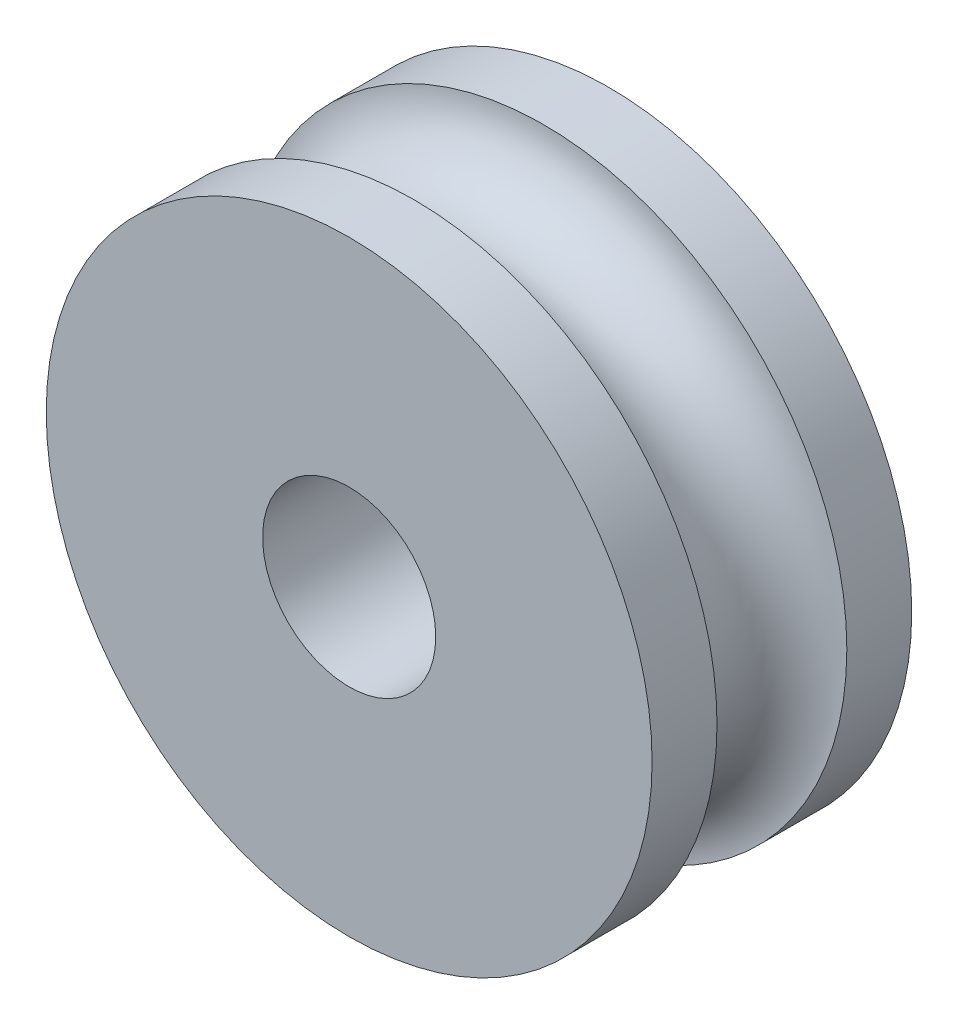
SolidWorks part; units mm, degrees
ref_plane "Alzado" through (0, 0, 0) normal (0, 0, 1) x (1, 0, 0)
ref_plane "Planta" through (0, 0, 0) normal (0, 1, 0) x (1, 0, 0)
ref_plane "Vista lateral" through (0, 0, 0) normal (1, 0, 0) x (0, 0, -1)
sketch "Croquis1" plane through (0, 0, 0) normal (0, 0, 1) x (1, 0, 0)
  circle A0 centre (0, 0) radius 3.5
  dimension "D1" = 7
extrude "Saliente-Extruir1" add sketch "Croquis1" along normal blind 3
ref_axis "Eje1" through (0, 0, 3) along (0, 0, -1)
sketch "Croquis2" plane through (0, 0, 0) normal (1, 0, 0) x (0, 0, -1)
  line L0 (0, 3.5) -> (-3, 3.5) construction
  circle A0 centre (-1.5, 3.5) radius 0.75
  dimension "D1" = 1.5
revolve "Cortar-Revolución1" cut sketch "Croquis2" angle 360 about axis through (0, 0, 3) along (0, 0, -1)
sketch "Croquis3" plane through (0, 0, 3) normal (0, 0, 1) x (1, 0, 0)
  circle A0 centre (0, 0) radius 1
  dimension "D1" = 2
extrude "Cortar-Extruir1" cut sketch "Croquis3" against normal through all
